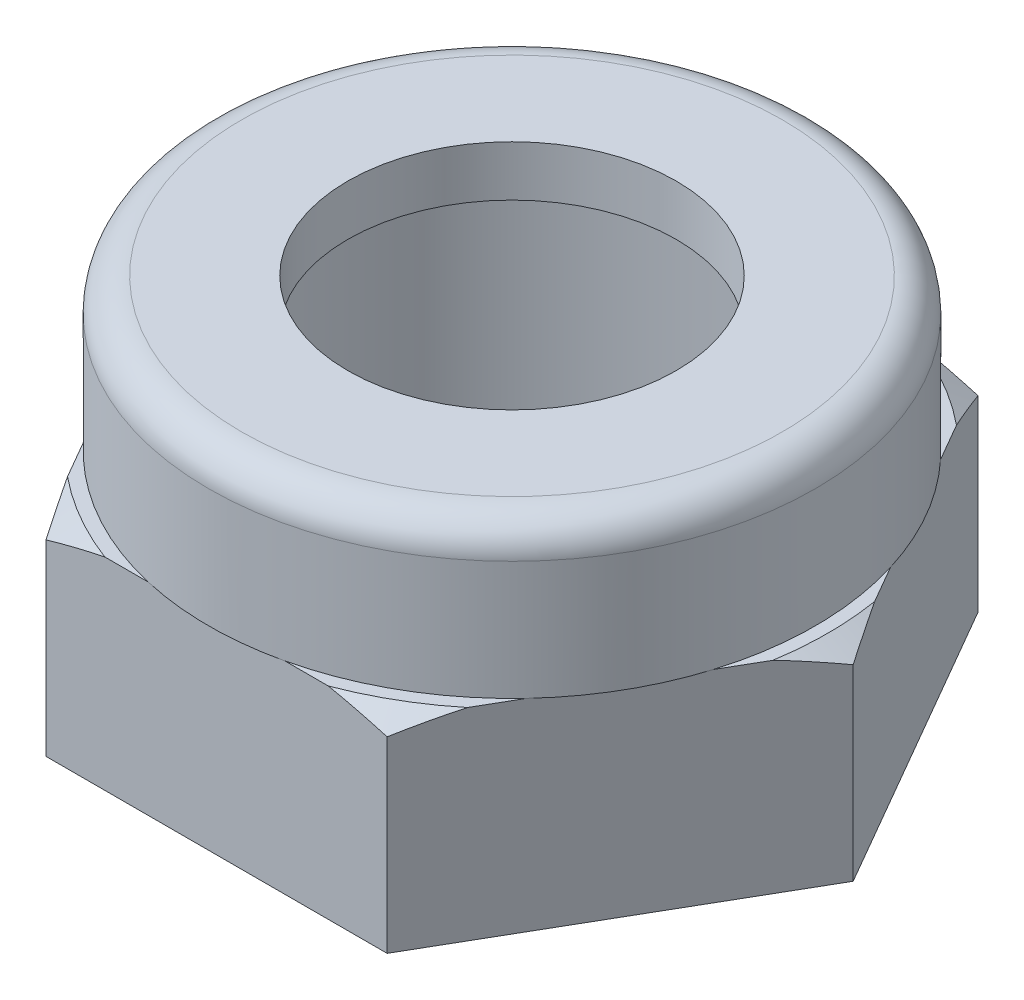
SolidWorks part; units mm, degrees
ref_plane "Front Plane" through (0, 0, 0) normal (0, 0, 1) x (1, 0, 0)
ref_plane "Top Plane" through (0, 0, 0) normal (0, 1, 0) x (1, 0, 0)
ref_plane "Right Plane" through (0, 0, 0) normal (1, 0, 0) x (0, 0, -1)
sketch "Sketch1" plane through (0, 0, 0) normal (1, 0, 0) x (0, 0, -1)
  line L0 (0, 0) -> (0, 38.6209) construction
  line L1 (0, 0) -> (52.5985, 0) construction
  line L2 (10, 0) -> (10, 12)
  line L3 (10, 12) -> (6.5, 12)
  line L4 (6.5, 12) -> (6.5, 14)
  line L5 (6.5, 14) -> (12, 14)
  line L6 (12, 14) -> (12, 8)
  line L7 (12, 8) -> (13.5, 8)
  line L8 (13.5, 8) -> (13.5, 0)
  line L9 (13.5, 0) -> (10, 0)
  dimension "D1" = 6.5
  dimension "D2" = 6
  dimension "D3" = 12
  dimension "D4" = 13.5
  dimension "D5" = 10
  dimension "D6" = 12
  dimension "D7" = 2
revolve "Revolve1" add sketch "Sketch1" angle 360 about L0
fillet "Fillet1" radius 1.3 1 edges at (0, 14, -12)
chamfer "Chamfer1" distance 1 angle 30 1 edges at (0, 8, -13.5)
sketch "Sketch2" plane through (0, 0, 0) normal (0, -1, 0) x (1, 0, 0)
  line L1 (-13.5, 0) -> (-6.75, -11.6913)
  line L2 (-6.75, -11.6913) -> (6.75, -11.6913)
  line L3 (6.75, -11.6913) -> (13.5, 0)
  line L4 (13.5, 0) -> (6.75, 11.6913)
  line L5 (6.75, 11.6913) -> (-6.75, 11.6913)
  line L6 (-6.75, 11.6913) -> (-13.5, 0)
  circle A0 centre (0, 0) radius 13.5 construction
extrude "Cut-Extrude1" cut sketch "Sketch2" against normal blind 8 flip side to cut
chamfer "Chamfer2" distance 1.6 angle 45 1 edges at (0, 0, -10)
